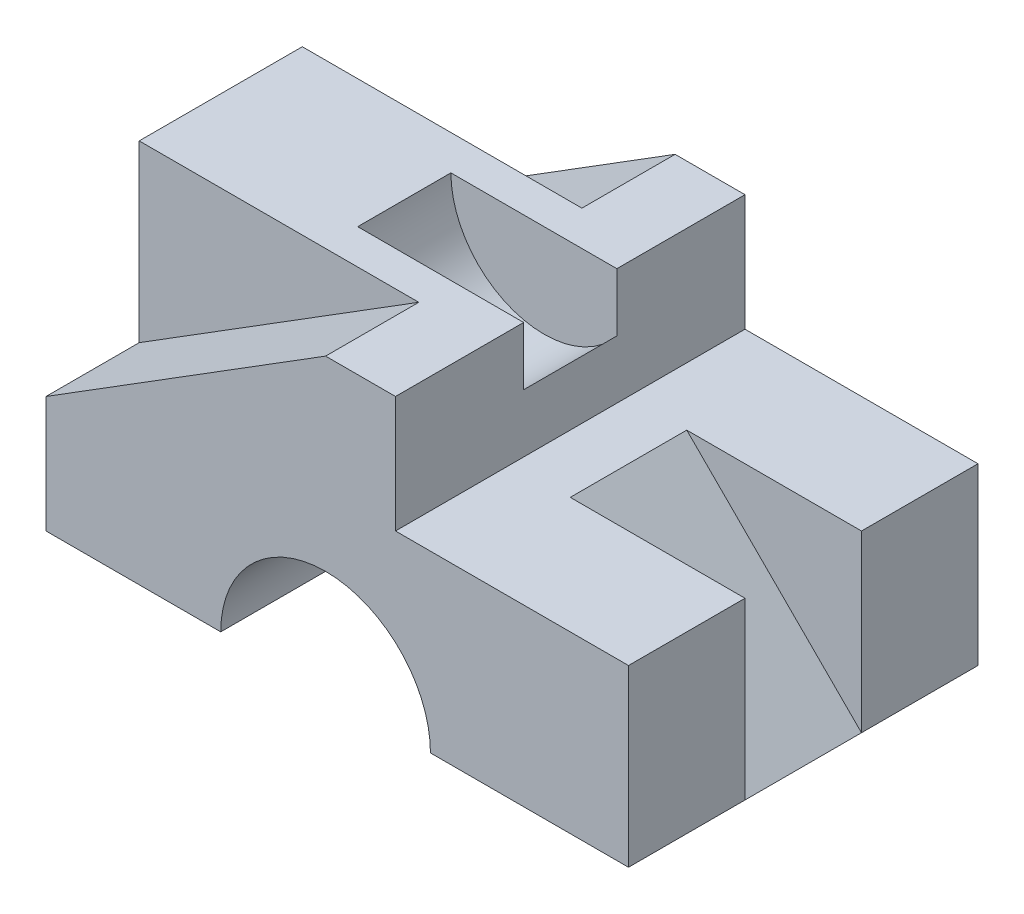
SolidWorks part; units mm, degrees
ref_plane "Front Plane" through (0, 0, 0) normal (0, 0, 1) x (1, 0, 0)
ref_plane "Top Plane" through (0, 0, 0) normal (0, 1, 0) x (1, 0, 0)
ref_plane "Right Plane" through (0, 0, 0) normal (1, 0, 0) x (0, 0, -1)
sketch "Sketch1" plane through (0, 0, 0) normal (0, 0, 1) x (1, 0, 0)
  line L0 (0, 0) -> (0, 20)
  line L2 (48, 50) -> (60, 50)
  line L3 (60, 50) -> (60, 30)
  line L4 (60, 30) -> (100, 30)
  line L5 (100, 30) -> (100, 0)
  line L7 (0, 0) -> (30, 0)
  line L8 (66, 0) -> (100, 0)
  line L9 (0, 20) -> (0, 50)
  line L10 (0, 50) -> (48, 50)
  arc A0 (30, 0) -> (66, 0) centre (48, 0) cw
  dimension "D3" = 18
  dimension "D1" = 100
  dimension "D2" = 30
  dimension "D4" = 34
  dimension "D5" = 30
  dimension "D6" = 50
  dimension "D7" = 60
  dimension "D8" = 20
extrude "Boss-Extrude1" add sketch "Sketch1" against normal mid plane 60
sketch "Sketch2" plane through (0, 0, 30) normal (0, 0, 1) x (1, 0, 0)
  line L0 (0, 20) -> (48, 50)
  line L1 (48, 50) -> (0, 50)
  line L2 (0, 50) -> (0, 20)
extrude "Cut-Extrude1" cut sketch "Sketch2" against normal blind 16
mirror "Mirror1" about plane through (0, 0, 0) normal (0, 0, 1) of "Cut-Extrude1"
sketch "Sketch3" plane through (0, 0, -30) normal (0, 0, -1) x (-1, 0, 0)
  line L0 (-70, 30) -> (-100, 0)
  line L1 (-60, 30) -> (-100, 30) construction
  line L2 (-100, 0) -> (-100, 30)
  line L3 (-100, 30) -> (-70, 30)
  dimension "D1" = 30
sketch "Sketch4" plane through (0, 0, 0) normal (0, 0, 1) x (1, 0, 0)
  line L0 (60, 50) -> (31.51, 50)
  line L1 (48, 50) -> (60, 50) construction
  line L2 (60, 50) -> (60, 30) construction
  line L3 (60, 40) -> (60, 50)
  arc A0 (31.51, 50) -> (60, 40) centre (47.51, 50) ccw
  dimension "D1" = 16
extrude "Cut-Extrude3" cut sketch "Sketch4" against normal mid plane 16
sketch "Sketch5" plane through (0, 0, 0) normal (0, 0, 1) x (1, 0, 0)
  line L0 (100, 0) -> (100, 30) construction
  line L1 (100, 30) -> (70, 30) construction
  line L2 (70, 30) -> (100, 0) construction
  line L3 (100, 0) -> (100, 30)
  line L4 (100, 30) -> (70, 30)
  line L5 (70, 30) -> (100, 0)
extrude "Cut-Extrude4" cut sketch "Sketch5" against normal mid plane 20
